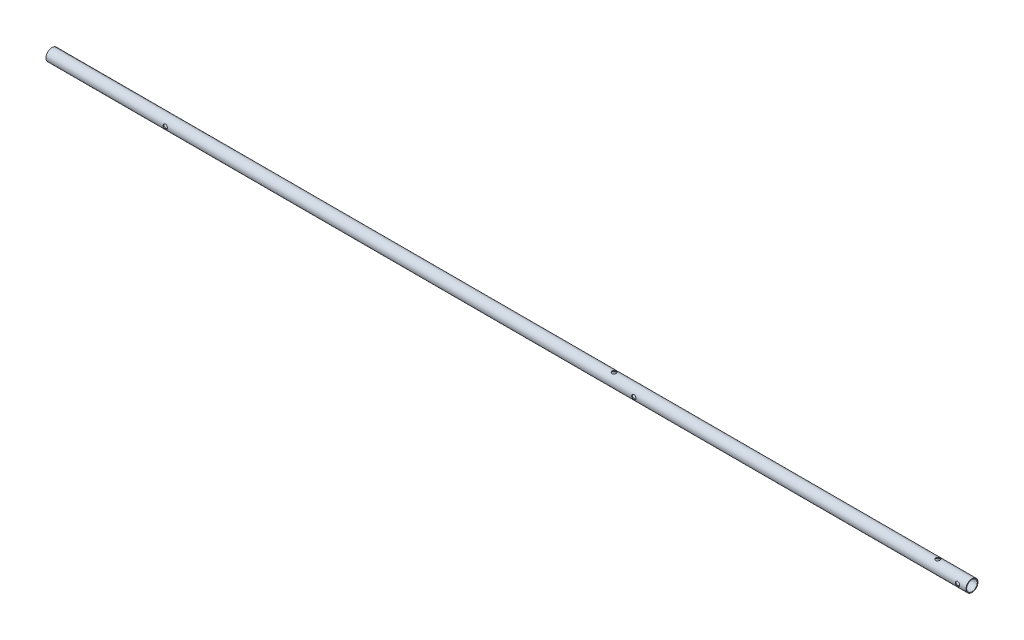
SolidWorks part; units mm, degrees
material "Galvanized Steel"
ref_plane "Front Plane" through (0, 0, 0) normal (0, 0, 1) x (1, 0, 0)
ref_plane "Top Plane" through (0, 0, 0) normal (0, 1, 0) x (1, 0, 0)
ref_plane "Right Plane" through (0, 0, 0) normal (1, 0, 0) x (0, 0, -1)
sketch "Sketch1" plane through (0, 0, 0) normal (1, 0, 0) x (0, 0, -1)
  circle A0 centre (0, 0) radius 7.8994
  circle A1 centre (0, 0) radius 8.9662
  dimension "D1" = 15.7988
  dimension "D2" = 17.9324
extrude "Boss-Extrude1" add sketch "Sketch1" along normal blind 1371.6
sketch "Sketch2" plane through (0, 0, 0) normal (0, 0, 1) x (1, 0, 0)
  line L0 (0, 7.8994) -> (0, -7.8994) construction
  line L1 (1371.6, -8.9662) -> (1371.6, 8.9662) construction
  line L2 (0, 8.9662) -> (0, -8.9662) construction
  circle A0 centre (876.3, 0) radius 3.175
  circle A1 centre (1358.9, 0) radius 3.175
  circle A2 centre (177.8, 0) radius 3.175
  dimension "D1" = 876.3
  dimension "D3" = 177.8
  dimension "D2" = 12.7
extrude "Cut-Extrude1" cut sketch "Sketch2" against normal through all and the other way through all
sketch "Sketch3" plane through (0, 0, 0) normal (0, 1, 0) x (1, 0, 0)
  line L0 (1371.6, -7.8994) -> (1371.6, 7.8994) construction
  circle A0 centre (1320.8, 0) radius 3.175
  circle A1 centre (838.2, 0) radius 3.175
  dimension "D1" = 533.4
  dimension "D2" = 50.8
extrude "Cut-Extrude2" cut sketch "Sketch3" against normal through all and the other way through all
